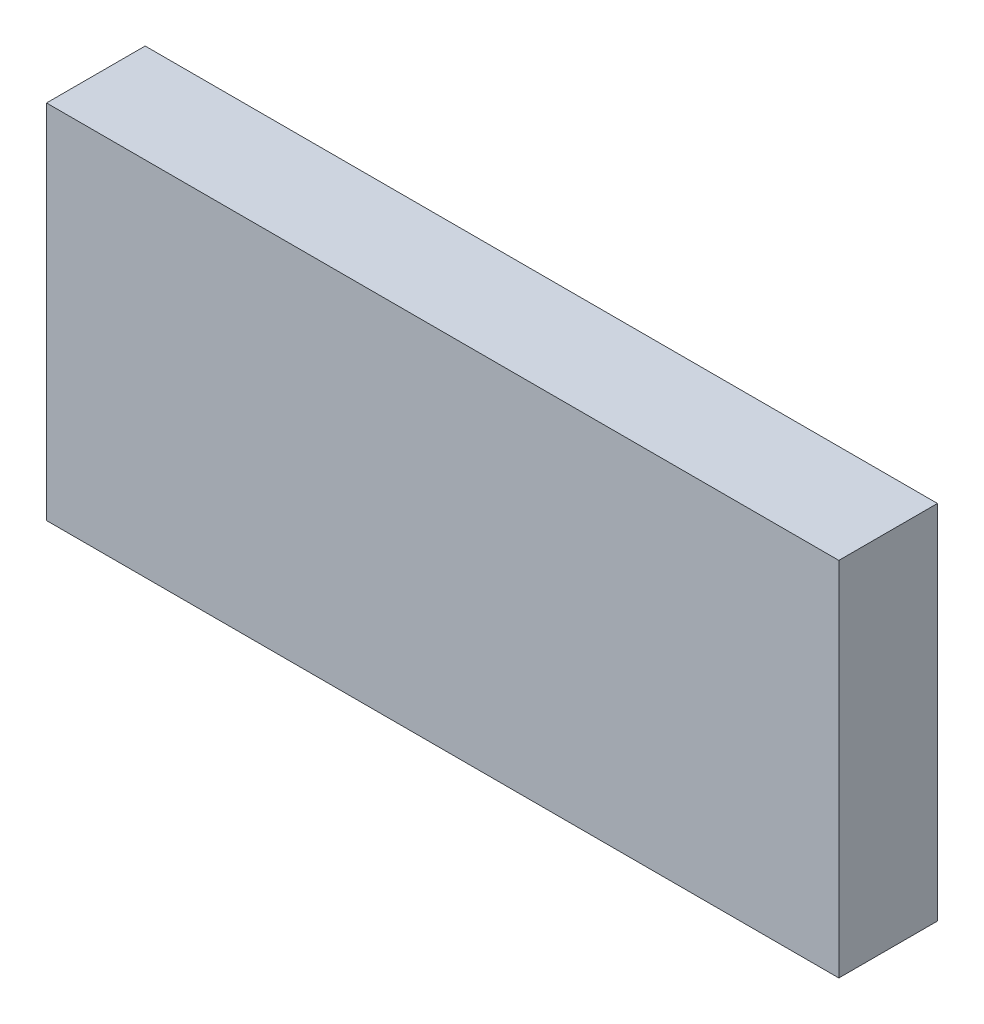
SolidWorks part; units mm, degrees
material "Polyurethane Foam Rigid"
ref_plane "X-Y Datum" through (0, 0, 0) normal (0, 0, 1) x (1, 0, 0)
ref_plane "X-Z Datum" through (0, 0, 0) normal (0, 1, 0) x (1, 0, 0)
ref_plane "Y-Z Datum" through (0, 0, 0) normal (1, 0, 0) x (0, 0, -1)
sketch "Sketch1" plane through (0, 0, 0) normal (0, 0, 1) x (1, 0, 0)
  line L1 (-153.0248, -69.85) -> (153.0248, -69.85)
  line L2 (-153.0248, -69.85) -> (-153.0248, 69.85)
  line L3 (-153.0248, 69.85) -> (153.0248, 69.85)
  line L4 (153.0248, -69.85) -> (153.0248, 69.85)
  line L5 (-153.0248, -69.85) -> (153.0248, 69.85) construction
  line L6 (-153.0248, 69.85) -> (153.0248, -69.85) construction
  point P0 (0, 0)
  dimension "D1" = 306.0497
  dimension "D2" = 139.7
extrude "Boss-Extrude1" add sketch "Sketch1" against normal blind 38.1
